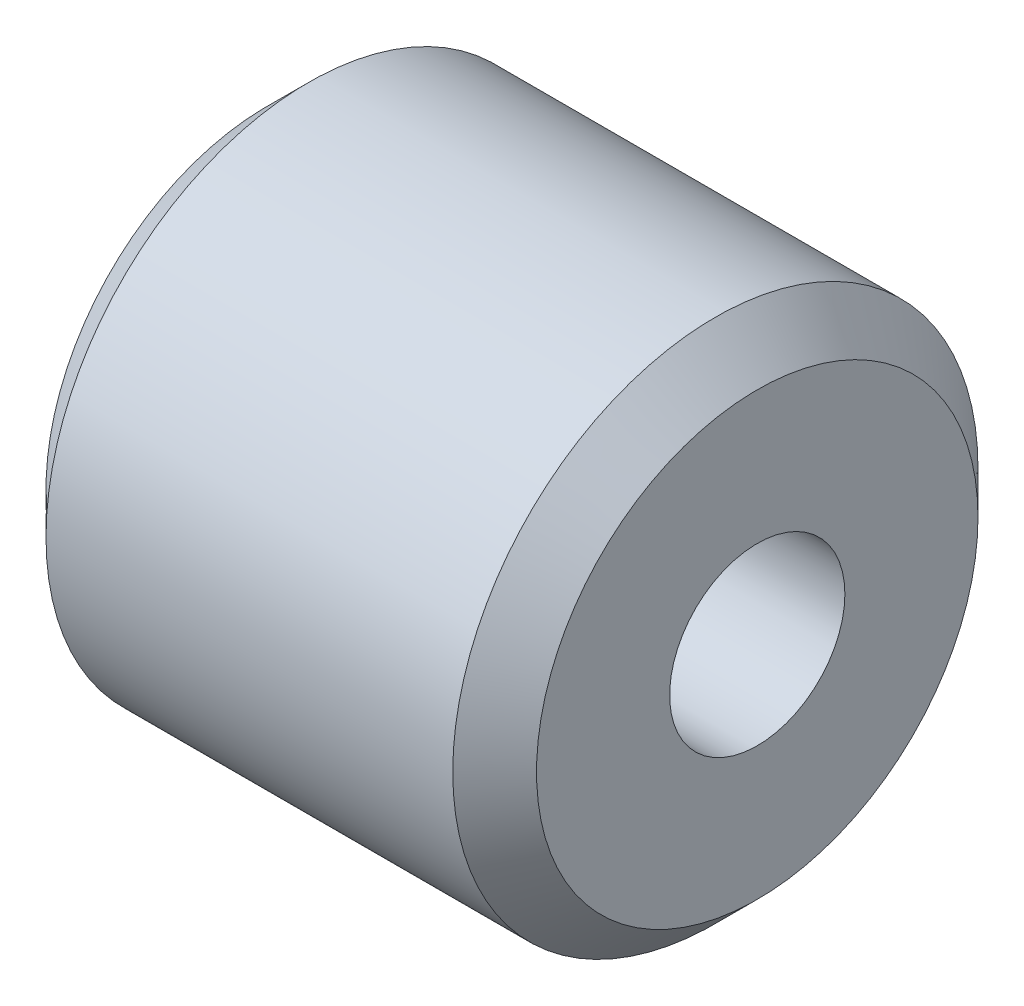
SolidWorks part; units mm, degrees
material "Ceramic Porcelain"
ref_plane "Front Plane" through (0, 0, 0) normal (0, 0, 1) x (1, 0, 0)
ref_plane "Top Plane" through (0, 0, 0) normal (0, 1, 0) x (1, 0, 0)
ref_plane "Right Plane" through (0, 0, 0) normal (1, 0, 0) x (0, 0, -1)
sketch "Sketch1" plane through (0, 0, 0) normal (1, 0, 0) x (0, 0, -1)
  circle A0 centre (0, 0.0782) radius 1.59
  circle A1 centre (0, 0.0782) radius 4.765
  dimension "D1" = 3.18
  dimension "D2" = 9.53
extrude "Boss-Extrude1" add sketch "Sketch1" along normal mid plane 8.9
chamfer "Chamfer1" distance 0.76 angle 45 2 edges at (-4.45, 0.0782, -4.765) (4.45, 0.0782, -4.765)
